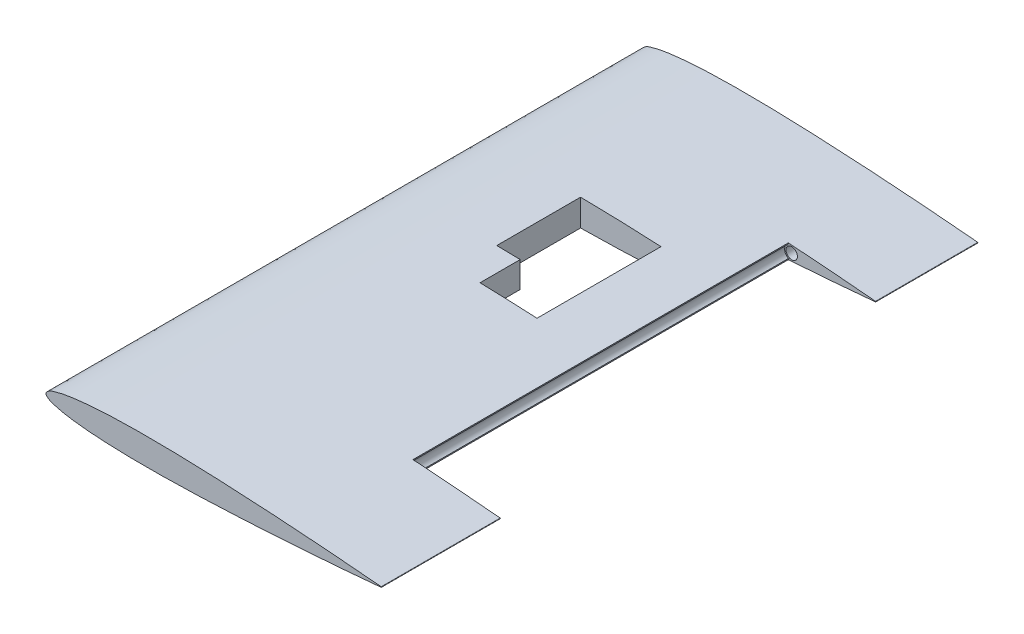
SolidWorks part; units mm, degrees
material "Manual Density from Real Component Stab Vert Legno"
ref_plane "Piano frontale" through (0, 0, 0) normal (0, 0, 1) x (1, 0, 0)
ref_plane "Piano superiore" through (0, 0, 0) normal (0, 1, 0) x (1, 0, 0)
ref_plane "Piano destro" through (0, 0, 0) normal (1, 0, 0) x (0, 0, -1)
curve "ProfiloBase"
  spline degree 3 poles (100, 0.084, 0) (98.3335, 0.2367, 0) (95.0012, 0.5422, 0) (88.3356, 1.1109, 0) (80.0033, 1.7636, 0) (70.003, 2.4579, 0) (60.0031, 3.0617, 0) (50.003, 3.5521, 0) (40.0026, 3.9029, 0) (31.667, 4.0253, 0) (24.9992, 3.9769, 0) (19.9978, 3.845, 0) (14.9934, 3.5925, 0) (10.8272, 3.2377, 0) (7.4891, 2.814, 0) (4.9936, 2.4037, 0) (2.8496, 1.8679, 0) (1.1654, 1.321, 0) (-0.6646, 0, 0) (1.1654, -1.321, 0) (2.8496, -1.8679, 0) (4.9936, -2.4037, 0) (7.4891, -2.814, 0) (10.8272, -3.2377, 0) (14.9934, -3.5925, 0) (19.9978, -3.845, 0) (24.9992, -3.9769, 0) (31.667, -4.0253, 0) (40.0026, -3.9029, 0) (50.003, -3.5521, 0) (60.0031, -3.0617, 0) (70.003, -2.4579, 0) (80.0033, -1.7636, 0) (88.3356, -1.1109, 0) (95.0012, -0.5422, 0) (98.3335, -0.2367, 0) (100, -0.084, 0) knots 0 0 0 0 0.024876 0.049742 0.099443 0.149112 0.198751 0.248359 0.297937 0.347491 0.372267 0.397051 0.421859 0.446731 0.45922 0.471791 0.48456 0.491195 0.5 0.508805 0.51544 0.528209 0.54078 0.553269 0.578141 0.602949 0.627733 0.652509 0.702063 0.751641 0.801249 0.850888 0.900557 0.950258 0.975124 1 1 1 1
sketch "Schizzo1" plane through (0, 0, 0) normal (0, 0, 1) x (1, 0, 0)
  line L0 (100, 0.084) -> (100, -0.084) construction
  arc A0 (100, 0.084) -> (100, -0.084) centre (100, 0) cw
  spline S0 degree 3 poles (1490.7083, 8861.9983) (489.6178, -110.9206) (294.0791, -16.4436) (88.3356, 1.1109) (80.0033, 1.7636) (70.003, 2.4579) (60.0031, 3.0617) (50.003, 3.5521) (40.0026, 3.9029) (31.667, 4.0253) (24.9992, 3.9769) (19.9978, 3.845) (14.9934, 3.5925) (10.8272, 3.2377) (7.4891, 2.814) (4.9936, 2.4037) (2.8496, 1.8679) (1.1654, 1.321) (-0.6646, 0) (1.1654, -1.321) (2.8496, -1.8679) (4.9936, -2.4037) (7.4891, -2.814) (10.8272, -3.2377) (14.9934, -3.5925) (19.9978, -3.845) (24.9992, -3.9769) (31.667, -4.0253) (40.0026, -3.9029) (50.003, -3.5521) (60.0031, -3.0617) (70.003, -2.4579) (80.0033, -1.7636) (88.3356, -1.1109) (294.0785, 16.4435) (489.6166, 110.92) (1490.6994, -8861.9185) knots -2.970007 -2.970007 -2.970007 -2.970007 0.024876 0.049742 0.099443 0.149112 0.198751 0.248359 0.297937 0.347491 0.372267 0.397051 0.421859 0.446731 0.45922 0.471791 0.48456 0.491195 0.5 0.508805 0.51544 0.528209 0.54078 0.553269 0.578141 0.602949 0.627733 0.652509 0.702063 0.751641 0.801249 0.850888 0.900557 0.950258 0.975124 3.969998 3.969998 3.969998 3.969998 only from (100, 0.084) to (100, -0.084) construction
  spline S1 degree 3 poles (100, 0.084) (98.3335, 0.2367) (95.0012, 0.5422) (88.3356, 1.1109) (80.0033, 1.7636) (70.003, 2.4579) (60.0031, 3.0617) (50.003, 3.5521) (40.0026, 3.9029) (31.667, 4.0253) (24.9992, 3.9769) (19.9978, 3.845) (14.9934, 3.5925) (10.8272, 3.2377) (7.4891, 2.814) (4.9936, 2.4037) (2.8496, 1.8679) (1.1654, 1.321) (-0.6646, 0) (1.1654, -1.321) (2.8496, -1.8679) (4.9936, -2.4037) (7.4891, -2.814) (10.8272, -3.2377) (14.9934, -3.5925) (19.9978, -3.845) (24.9992, -3.9769) (31.667, -4.0253) (40.0026, -3.9029) (50.003, -3.5521) (60.0031, -3.0617) (70.003, -2.4579) (80.0033, -1.7636) (88.3356, -1.1109) (95.0012, -0.5422) (98.3335, -0.2367) (100, -0.084) knots 0 0 0 0 0.024876 0.049742 0.099443 0.149112 0.198751 0.248359 0.297937 0.347491 0.372267 0.397051 0.421859 0.446731 0.45922 0.471791 0.48456 0.491195 0.5 0.508805 0.51544 0.528209 0.54078 0.553269 0.578141 0.602949 0.627733 0.652509 0.702063 0.751641 0.801249 0.850888 0.900557 0.950258 0.975124 1 1 1 1
  point P5 (100, 0)
extrude "FoamBassa" add sketch "Schizzo1" along normal blind 30.5
sketch "Schizzo2" plane through (0, 0, 30.5) normal (0, 0, 1) x (1, 0, 0)
  line L0 (75, 2.1072) -> (75, -2.1072) construction
  arc A4 (75, 2.1072) -> (75, -2.1072) centre (75, 0) ccw
  spline S1 degree 3 poles (774.5938, 2905.893) (370.1816, -60.6448) (232.5901, -11.1972) (88.3356, 1.1109) (80.0033, 1.7636) (70.003, 2.4579) (60.0031, 3.0617) (50.003, 3.5521) (40.0026, 3.9029) (31.667, 4.0253) (24.9992, 3.9769) (19.9978, 3.845) (14.9934, 3.5925) (10.8272, 3.2377) (7.4891, 2.814) (4.9936, 2.4037) (2.8496, 1.8679) (1.1654, 1.321) (-0.6646, 0) (1.1654, -1.321) (2.8496, -1.8679) (4.9936, -2.4037) (7.4891, -2.814) (10.8272, -3.2377) (14.9934, -3.5925) (19.9978, -3.845) (24.9992, -3.9769) (31.667, -4.0253) (40.0026, -3.9029) (50.003, -3.5521) (60.0031, -3.0617) (70.003, -2.4579) (80.0033, -1.7636) (88.3356, -1.1109) (232.5893, 11.1971) (370.1799, 60.6442) (774.5865, -2905.8392) knots -2.052665 -2.052665 -2.052665 -2.052665 0.024876 0.049742 0.099443 0.149112 0.198751 0.248359 0.297937 0.347491 0.372267 0.397051 0.421859 0.446731 0.45922 0.471791 0.48456 0.491195 0.5 0.508805 0.51544 0.528209 0.54078 0.553269 0.578141 0.602949 0.627733 0.652509 0.702063 0.751641 0.801249 0.850888 0.900557 0.950258 0.975124 3.052652 3.052652 3.052652 3.052652 only from (100, 0.084) to (100, -0.084) construction
  spline S2 degree 3 poles (75, 2.1072) (73.3336, 2.2229) (68.3351, 2.5586) (60.0031, 3.0617) (50.003, 3.5521) (40.0026, 3.9029) (31.667, 4.0253) (24.9992, 3.9769) (19.9978, 3.845) (14.9934, 3.5925) (10.8272, 3.2377) (7.4891, 2.814) (4.9936, 2.4037) (2.8496, 1.8679) (1.1654, 1.321) (-0.6646, 0) (1.1654, -1.321) (2.8496, -1.8679) (4.9936, -2.4037) (7.4891, -2.814) (10.8272, -3.2377) (14.9934, -3.5925) (19.9978, -3.845) (24.9992, -3.9769) (31.667, -4.0253) (40.0026, -3.9029) (50.003, -3.5521) (60.0031, -3.0617) (68.3351, -2.5586) (73.3336, -2.2229) (75, -2.1072) knots 0.124282 0.124282 0.124282 0.124282 0.149112 0.198751 0.248359 0.297937 0.347491 0.372267 0.397051 0.421859 0.446731 0.45922 0.471791 0.48456 0.491195 0.5 0.508805 0.51544 0.528209 0.54078 0.553269 0.578141 0.602949 0.627733 0.652509 0.702063 0.751641 0.801249 0.850888 0.875718 0.875718 0.875718 0.875718
  dimension "D1" = 4.2144
extrude "FoamMedia" add sketch "Schizzo2" along normal blind 112
sketch "Schizzo4" plane through (0, 0, 142.5) normal (0, 0, 1) x (1, 0, 0)
  line L1 (75, 2.1762) -> (74, 2.1762)
  line L2 (75, 2.1762) -> (75, -2.1762)
  line L3 (75, -2.1762) -> (74, -2.1762)
  line L4 (74, 2.1762) -> (74, -2.1762)
  spline S0 degree 3 poles (75, 2.1072) (73.3336, 2.2229) (68.3351, 2.5586) (60.0031, 3.0617) (50.003, 3.5521) (40.0026, 3.9029) (31.667, 4.0253) (24.9992, 3.9769) (19.9978, 3.845) (14.9934, 3.5925) (10.8272, 3.2377) (7.4891, 2.814) (4.9936, 2.4037) (2.8496, 1.8679) (1.1654, 1.321) (-0.6646, 0) (1.1654, -1.321) (2.8496, -1.8679) (4.9936, -2.4037) (7.4891, -2.814) (10.8272, -3.2377) (14.9934, -3.5925) (19.9978, -3.845) (24.9992, -3.9769) (31.667, -4.0253) (40.0026, -3.9029) (50.003, -3.5521) (60.0031, -3.0617) (68.3351, -2.5586) (73.3336, -2.2229) (75, -2.1072) knots 0.124282 0.124282 0.124282 0.124282 0.149112 0.198751 0.248359 0.297937 0.347491 0.372267 0.397051 0.421859 0.446731 0.45922 0.471791 0.48456 0.491195 0.5 0.508805 0.51544 0.528209 0.54078 0.553269 0.578141 0.602949 0.627733 0.652509 0.702063 0.751641 0.801249 0.850888 0.875718 0.875718 0.875718 0.875718 construction
  dimension "D1" = 1
extrude "SmussoParteMobile" cut sketch "Schizzo4" against normal up to surface (112 mm away) up to face at (86.9942, -0.5058, 30.5)
sketch "Schizzo6" plane through (0, 0, 142.5) normal (0, 0, 1) x (1, 0, 0)
  arc A0 (100, 0.084) -> (100, -0.084) centre (100, 0) cw
  spline S0 degree 3 poles (633.0503, 1915.9881) (335.6221, -48.8321) (214.9188, -9.6895) (88.3356, 1.1109) (80.0033, 1.7636) (70.003, 2.4579) (60.0031, 3.0617) (50.003, 3.5521) (40.0026, 3.9029) (31.667, 4.0253) (24.9992, 3.9769) (19.9978, 3.845) (14.9934, 3.5925) (10.8272, 3.2377) (7.4891, 2.814) (4.9936, 2.4037) (2.8496, 1.8679) (1.1654, 1.321) (-0.6646, 0) (1.1654, -1.321) (2.8496, -1.8679) (4.9936, -2.4037) (7.4891, -2.814) (10.8272, -3.2377) (14.9934, -3.5925) (19.9978, -3.845) (24.9992, -3.9769) (31.667, -4.0253) (40.0026, -3.9029) (50.003, -3.5521) (60.0031, -3.0617) (70.003, -2.4579) (80.0033, -1.7636) (88.3356, -1.1109) (214.9185, 9.6894) (335.6215, 48.8319) (633.0478, -1915.9718) knots -1.78903 -1.78903 -1.78903 -1.78903 0.024876 0.049742 0.099443 0.149112 0.198751 0.248359 0.297937 0.347491 0.372267 0.397051 0.421859 0.446731 0.45922 0.471791 0.48456 0.491195 0.5 0.508805 0.51544 0.528209 0.54078 0.553269 0.578141 0.602949 0.627733 0.652509 0.702063 0.751641 0.801249 0.850888 0.900557 0.950258 0.975124 2.789025 2.789025 2.789025 2.789025 only from (100, 0.084) to (100, -0.084) construction
  spline S1 degree 3 poles (100, 0.084) (98.3335, 0.2367) (95.0012, 0.5422) (88.3356, 1.1109) (80.0033, 1.7636) (70.003, 2.4579) (60.0031, 3.0617) (50.003, 3.5521) (40.0026, 3.9029) (31.667, 4.0253) (24.9992, 3.9769) (19.9978, 3.845) (14.9934, 3.5925) (10.8272, 3.2377) (7.4891, 2.814) (4.9936, 2.4037) (2.8496, 1.8679) (1.1654, 1.321) (-0.6646, 0) (1.1654, -1.321) (2.8496, -1.8679) (4.9936, -2.4037) (7.4891, -2.814) (10.8272, -3.2377) (14.9934, -3.5925) (19.9978, -3.845) (24.9992, -3.9769) (31.667, -4.0253) (40.0026, -3.9029) (50.003, -3.5521) (60.0031, -3.0617) (70.003, -2.4579) (80.0033, -1.7636) (88.3356, -1.1109) (95.0012, -0.5422) (98.3335, -0.2367) (100, -0.084) knots 0 0 0 0 0.024876 0.049742 0.099443 0.149112 0.198751 0.248359 0.297937 0.347491 0.372267 0.397051 0.421859 0.446731 0.45922 0.471791 0.48456 0.491195 0.5 0.508805 0.51544 0.528209 0.54078 0.553269 0.578141 0.602949 0.627733 0.652509 0.702063 0.751641 0.801249 0.850888 0.900557 0.950258 0.975124 1 1 1 1
extrude "FoamAlta" add sketch "Schizzo6" along normal blind 35.5
sketch "Schizzo5" plane through (0, 0, 30.5) normal (0, 0, 1) x (1, 0, 0)
  circle A0 centre (75, 0) radius 1.7
  dimension "D1" = 3.4
extrude "ForoPernoRuddevator" cut sketch "Schizzo5" against normal through all and the other way offset from surface (142.5 mm away) 5 other way up to face at (100.042, 0.042, 178)
ref_plane "PianoDado" through (0, 0, 6) normal (0, 0, -1) x (-1, 0, 0)
ref_plane "PianoAusiliario" through (0, -10, 0) normal (0, 1, 0) x (1, 0, 0)
sketch "Schizzo12" plane through (0, -10, 0) normal (0, 1, 0) x (1, 0, 0)
  line L0 (57, -76.5) -> (57, -88.5)
  line L1 (33, -76.5) -> (57, -76.5) construction
  line L2 (33, -76.5) -> (33, -51.5)
  line L3 (33, -51.5) -> (57, -51.5)
  line L4 (57, -76.5) -> (57, -51.5)
  line L5 (57, -88.5) -> (40, -88.5)
  line L6 (40, -88.5) -> (40, -76.5)
  line L7 (40, -76.5) -> (33, -76.5)
  line L8 (57, -86.5) -> (74, -86.5) construction
  line L9 (74, -142.5) -> (74, -30.5) construction
  dimension "D1" = 24
  dimension "D2" = 25
  dimension "D3" = 17
  dimension "D4" = 12
  dimension "D5" = 2
  dimension "D6" = 17
extrude "ForoServomotore" cut sketch "Schizzo12" along normal through all
sketch "Schizzo14" plane through (0, 0, 0) normal (0, 0, -1) x (-1, 0, 0)
  line L1 (-15, -2) -> (-55, -2)
  line L2 (-15, -2) -> (-15, 2)
  line L3 (-15, 2) -> (-55, 2)
  line L4 (-55, -2) -> (-55, 2)
  line L5 (-15, -2) -> (-55, 2) construction
  line L6 (-15, 2) -> (-55, -2) construction
  point P0 (-35, 0)
  dimension "D1" = 4
  dimension "D2" = 40
  dimension "D3" = 15
extrude "TaglioSpina" cut sketch "Schizzo14" against normal blind 18
